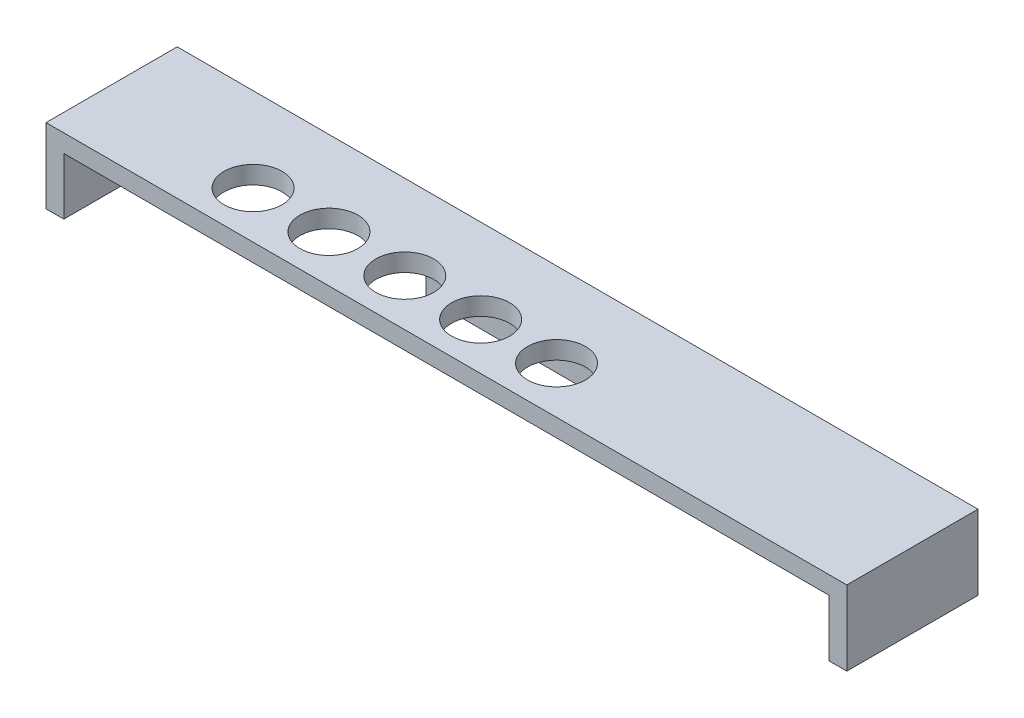
SolidWorks part; units mm, degrees
ref_plane "Front Plane" through (0, 0, 0) normal (0, 0, 1) x (1, 0, 0)
ref_plane "Top Plane" through (0, 0, 0) normal (0, 1, 0) x (1, 0, 0)
ref_plane "Right Plane" through (0, 0, 0) normal (1, 0, 0) x (0, 0, -1)
sketch "Sketch1" plane through (0, 0, 0) normal (0, 1, 0) x (1, 0, 0)
  line L0 (0, 0) -> (0, 14.7)
  line L1 (0, 14.7) -> (89.725, 14.7)
  line L2 (89.725, 14.7) -> (89.725, 0)
  line L3 (89.725, 0) -> (87.725, 0)
  line L4 (87.725, 0) -> (87.725, 12.7)
  line L5 (87.725, 12.7) -> (2, 12.7)
  line L6 (2, 12.7) -> (2, 0)
  line L7 (2, 0) -> (0, 0)
  line L8 (2, 12.7) -> (2, 14.7) construction
  dimension "D1" = 2
  dimension "D2" = 12.7
  dimension "D3" = 85.725
extrude "Boss-Extrude1" add sketch "Sketch1" along normal blind 3.9688
sketch "Sketch2" plane through (0, 3.9688, 0) normal (0, 1, 0) x (1, 0, 0)
  line L1 (0, 14.7) -> (89.725, 14.7)
  line L2 (0, 14.7) -> (0, 0)
  line L3 (0, 0) -> (89.725, 0)
  line L4 (89.725, 14.7) -> (89.725, 0)
extrude "Boss-Extrude2" add sketch "Sketch2" along normal blind 2
sketch "Sketch3" plane through (0, 5.9688, 0) normal (0, 1, 0) x (1, 0, 0)
  line L0 (21.2, 5.25) -> (17.95, 2) construction
  line L1 (0, 0) -> (89.725, 0) construction
  line L2 (17.95, 5.25) -> (81.1776, 5.25) construction
  line L3 (14.7, 5.25) -> (17.95, 5.25) construction
  circle A0 centre (17.95, 5.25) radius 3.25
  circle A2 centre (26.45, 5.25) radius 3.25
  circle A3 centre (34.95, 5.25) radius 3.25
  circle A4 centre (43.45, 5.25) radius 3.25
  circle A5 centre (51.95, 5.25) radius 3.25
  dimension "D1" = 6.5
  dimension "D2" = 2
  dimension "D3" = 12.7
  dimension "D4" = 5
extrude "Cut-Extrude1" cut sketch "Sketch3" against normal through all
sketch "Sketch4" plane through (0, 0, 0) normal (0, -1, 0) x (-1, 0, 0)
  line L0 (0, 0) -> (-2, 0) construction
  line L1 (-89.725, 14.7) -> (-87.725, 14.7)
  line L2 (-89.725, 14.7) -> (-89.725, 0)
  line L3 (-89.725, 0) -> (-87.725, 0)
  line L4 (-87.725, 14.7) -> (-87.725, 0)
  line L5 (0, 14.7) -> (-2, 14.7)
  line L6 (0, 14.7) -> (0, 0)
  line L7 (0, 0) -> (-2, 0)
  line L8 (-2, 14.7) -> (-2, 0)
  line L9 (-2, 0) -> (-2, 12.7) construction
  line L10 (-89.725, 14.7) -> (0, 14.7) construction
  line L11 (-59.8625, 14.7) -> (-29.8625, 14.7)
  line L12 (-59.8625, 14.7) -> (-59.8625, 12.7)
  line L13 (-59.8625, 12.7) -> (-29.8625, 12.7)
  line L14 (-29.8625, 14.7) -> (-29.8625, 12.7)
  line L16 (-2, 12.7) -> (-87.725, 12.7) construction
  line L17 (-59.8625, 14.7) -> (-87.725, 14.7) construction
  line L18 (-29.8625, 14.7) -> (-2, 14.7) construction
  dimension "D1" = 30
extrude "Boss-Extrude3" add sketch "Sketch4" along normal blind 2.4
